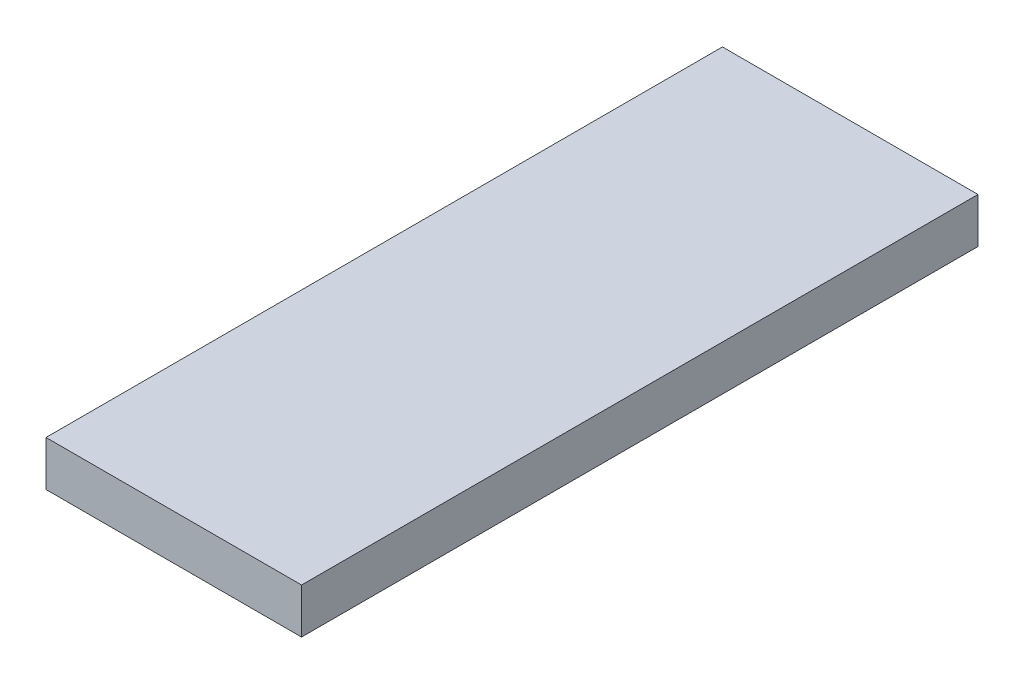
SolidWorks part; units mm, degrees
ref_plane "Front Plane" through (0, 0, 0) normal (0, 0, 1) x (1, 0, 0)
ref_plane "Top Plane" through (0, 0, 0) normal (0, 1, 0) x (1, 0, 0)
ref_plane "Right Plane" through (0, 0, 0) normal (1, 0, 0) x (0, 0, -1)
sketch "Sketch1" plane through (0, 0, 0) normal (0, 1, 0) x (1, 0, 0)
  line L1 (8.5, 22.5) -> (-8.5, 22.5)
  line L2 (8.5, 22.5) -> (8.5, -22.5)
  line L3 (8.5, -22.5) -> (-8.5, -22.5)
  line L4 (-8.5, 22.5) -> (-8.5, -22.5)
  line L5 (8.5, 22.5) -> (-8.5, -22.5) construction
  line L6 (8.5, -22.5) -> (-8.5, 22.5) construction
  point P0 (0, 0)
  dimension "D1" = 45
  dimension "D2" = 17
extrude "Boss-Extrude1" add sketch "Sketch1" along normal blind 3
